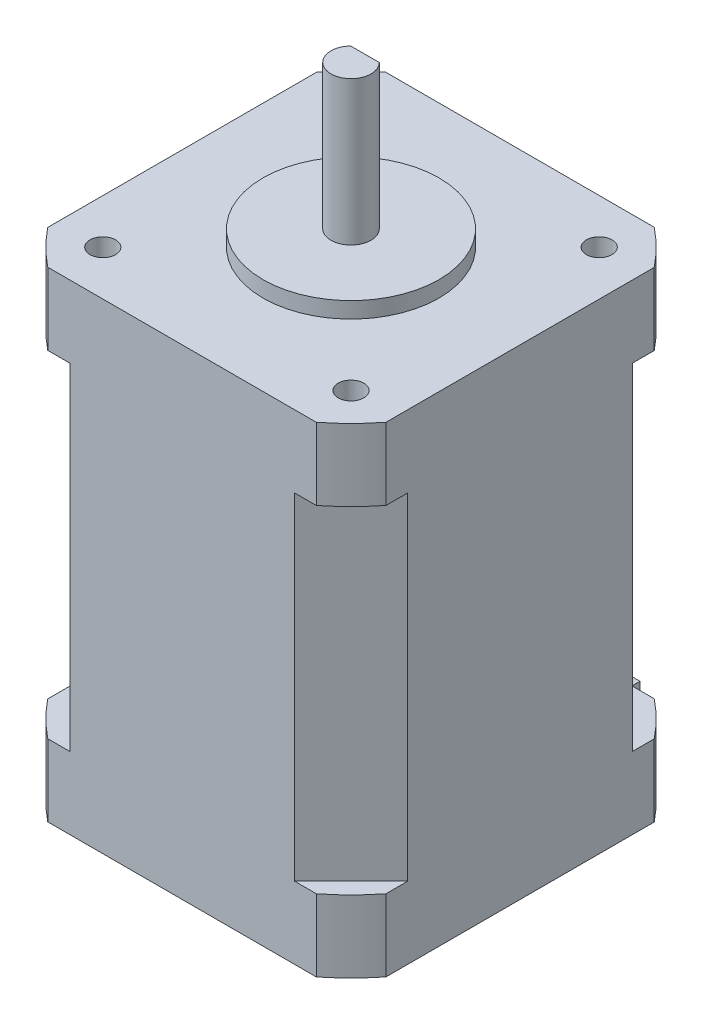
SolidWorks part; units mm, degrees
ref_plane "前视基准面" through (0, 0, 0) normal (0, 0, 1) x (1, 0, 0)
ref_plane "上视基准面" through (0, 0, 0) normal (0, 1, 0) x (1, 0, 0)
ref_plane "右视基准面" through (0, 0, 0) normal (1, 0, 0) x (0, 0, -1)
other "Configuration Table"
sketch "草图2" plane through (0, 0, 0) normal (0, 1, 0) x (1, 0, 0)
  line L0 (-14.0127, 22.4478) -> (-21.0838, 15.3767)
  line L1 (-14.0127, -19.7522) -> (14.0451, -19.7522)
  line L2 (-21.0838, -12.6812) -> (-21.0838, 15.3767)
  line L3 (-14.0127, 22.4478) -> (14.0451, 22.4478)
  line L4 (21.1162, -12.6812) -> (21.1162, 15.3767)
  line L5 (-18.4442, -15.3208) -> (19.9343, 16.5586) construction
  line L6 (-17.2245, 19.2359) -> (15.9664, -17.8309) construction
  line L7 (21.1162, 15.3767) -> (14.0451, 22.4478)
  line L8 (14.0451, -19.7522) -> (21.1162, -12.6812)
  line L9 (-21.0838, -12.6812) -> (-14.0127, -19.7522)
  point P0 (0, 0)
  point P17 (0.0162, 1.3478)
  dimension "D1" = 10
  dimension "D2" = 42.2
  dimension "D3" = 135
  dimension "D5" = 4
extrude "凸台-拉伸1" add sketch "草图2" along normal blind 60
sketch "草图5" plane through (0, 60, 0) normal (0, 1, 0) x (1, 0, 0)
  line L0 (21.1162, -12.6812) -> (21.1162, 15.3767) construction
  line L1 (-16.7762, 22.4478) -> (16.7762, 22.4478)
  line L2 (-21.0838, 18.1444) -> (-21.0838, -15.4488)
  line L3 (-16.7762, -19.7522) -> (16.7762, -19.7522)
  line L4 (21.1162, 18.1036) -> (21.1162, -15.4081)
  line L5 (14.0451, 22.4478) -> (-14.0127, 22.4478) construction
  line L6 (-21.0838, 15.3767) -> (-21.0838, -12.6812) construction
  line L7 (-14.0127, -19.7522) -> (14.0451, -19.7522) construction
  arc A0 (-16.7762, 22.4478) -> (-21.0838, 18.1444) centre (0, 1.3478) ccw
  arc A1 (-21.0838, -15.4488) -> (-16.7762, -19.7522) centre (0, 1.3478) ccw
  arc A2 (16.7762, -19.7522) -> (21.1162, -15.4081) centre (0, 1.3478) ccw
  arc A3 (21.1162, 18.1036) -> (16.7762, 22.4478) centre (0, 1.3478) ccw
  dimension "D1" = 21.1
extrude "凸台-拉伸2" add sketch "草图5" against normal blind 9 contours A3 L1 A0 L2 A1 L3 A2 L4
ref_plane "基准面1" through (0, 30, 0) normal (0, 1, 0) x (1, 0, 0)
mirror "镜向1" about plane through (0, 30, 0) normal (0, 1, 0) of "凸台-拉伸2"
sketch "草图7" plane through (0, 60, 0) normal (0, 1, 0) x (1, 0, 0)
  line L0 (16.7762, 22.4478) -> (-16.7762, 22.4478) construction
  circle A0 centre (0, 1.3478) radius 11
  dimension "D1" = 22
  dimension "D2" = 21.1
extrude "凸台-拉伸3" add sketch "草图7" along normal blind 2
sketch "草图8" plane through (0, 62, 0) normal (0, 1, 0) x (1, 0, 0)
  line L0 (16.7762, 22.4478) -> (-16.7762, 22.4478) construction
  circle A0 centre (0, 1.3478) radius 2.5
  dimension "D1" = 5
  dimension "D2" = 21.1
extrude "凸台-拉伸4" add sketch "草图8" along normal blind 18
sketch "草图9" plane through (0, 80, 0) normal (0, 1, 0) x (1, 0, 0)
  line L0 (-1.7854, 3.0978) -> (1.7854, 3.0978)
  arc A0 (1.7854, 3.0978) -> (-1.7854, 3.0978) centre (0, 1.3478) ccw
  dimension "D1" = 1.75
extrude "切除-拉伸1" cut sketch "草图9" against normal blind 15
sketch "草图10" plane through (0, 60, 0) normal (0, 1, 0) x (1, 0, 0)
  circle A0 centre (-15.5, 16.8478) radius 1.6
  circle A2 centre (15.5, 16.8478) radius 1.6
  circle A3 centre (15.5, -14.1522) radius 1.6
  circle A4 centre (-15.5, -14.1522) radius 1.6
  point P2 (0, 1.3478)
  point P13 (0, 1.3478)
  dimension "D1" = 3.2
  dimension "D2" = 15.5
  dimension "D3" = 15.5
  dimension "D4" = 4
extrude "切除-拉伸2" cut sketch "草图10" against normal blind 4.5
sketch "草图11" plane through (0, 0, -22.4478) normal (0, 0, -1) x (-1, 0, 0)
  line L0 (10, 0) -> (-10, 0)
  line L1 (-16.7762, 0) -> (16.7762, 0) construction
  line L2 (-10, 0) -> (-10, 5)
  line L3 (-10, 5) -> (-9, 5)
  line L4 (-9, 5) -> (-9, 1)
  line L5 (-9, 1) -> (9, 1)
  line L6 (0, 0) -> (0, 4.3168) construction
  line L7 (9, 5) -> (9, 1)
  line L8 (10, 5) -> (9, 5)
  line L9 (10, 0) -> (10, 5)
  point P11 (0, 1)
  dimension "D1" = 1
  dimension "D2" = 20
  dimension "D3" = 5
  dimension "D4" = 1
extrude "凸台-拉伸5" add sketch "草图11" along normal blind 5
sketch "草图12" plane through (0, 0, 0) normal (0, -1, 0) x (1, 0, 0)
  line L0 (-7.1447, -27.4478) -> (-7.1447, -24.4478)
  line L1 (10, -27.4478) -> (-10, -27.4478) construction
  line L2 (-7.1447, -24.4478) -> (-7.6447, -24.4478)
  line L3 (-7.6447, -24.4478) -> (-7.6447, -26.4478)
  line L4 (-7.6447, -26.4478) -> (-8.1447, -26.4478)
  line L5 (-8.1447, -26.4478) -> (-7.6447, -27.4478)
  line L6 (-7.6447, -27.4478) -> (-7.1447, -27.4478)
  line L7 (0, -27.6121) -> (0, -20.757) construction
  line L8 (7.6447, -27.4478) -> (7.1447, -27.4478)
  line L9 (8.1447, -26.4478) -> (7.6447, -27.4478)
  line L10 (7.6447, -26.4478) -> (8.1447, -26.4478)
  line L11 (7.6447, -24.4478) -> (7.6447, -26.4478)
  line L12 (7.1447, -24.4478) -> (7.6447, -24.4478)
  line L13 (7.1447, -27.4478) -> (7.1447, -24.4478)
  dimension "D1" = 0.5
  dimension "D2" = 0.5
  dimension "D3" = 0.5
  dimension "D4" = 1
  dimension "D5" = 3
extrude "切除-拉伸3" cut sketch "草图12" against normal blind 5
sketch "草图13" plane through (0, 0, -22.4478) normal (0, 0, -1) x (-1, 0, 0)
  line L0 (0, 0) -> (0, 8.1139) construction
  line L1 (9, 1) -> (-9, 1) construction
  circle A0 centre (-1.27, 3.54) radius 0.5623
  circle A1 centre (-3.81, 3.54) radius 0.5623
  circle A2 centre (-6.35, 3.54) radius 0.5623
  circle A3 centre (6.35, 3.54) radius 0.5623
  circle A4 centre (3.81, 3.54) radius 0.5623
  circle A5 centre (1.27, 3.54) radius 0.5623
  dimension "D1" = 2.54
  dimension "D3" = 2.54
  dimension "D2" = 3
extrude "凸台-拉伸6" add sketch "草图13" along normal blind 5
sketch "草图14" plane through (0, 0, 0) normal (0, -1, 0) x (1, 0, 0)
  line L0 (21.1162, 15.4081) -> (21.1162, -18.1036) construction
  circle A0 centre (14.1162, 12.7522) radius 2
  circle A1 centre (12.7522, -14.1162) radius 2
  circle A2 centre (-14.1162, -12.7522) radius 2
  circle A3 centre (-12.7522, 14.1162) radius 2
  circle A4 centre (14.1162, 12.7522) radius 1.75
  circle A5 centre (12.7522, -14.1162) radius 1.75
  circle A6 centre (-14.1162, -12.7522) radius 1.75
  circle A7 centre (-12.7522, 14.1162) radius 1.75
  point P14 (0, 0)
  point P22 (0, 0)
  dimension "D4" = 4
  dimension "D5" = 3.5
  dimension "D1" = 7
  dimension "D2" = 7
  dimension "D3" = 4
  dimension "D6" = 4
extrude "切除-拉伸4" cut sketch "草图14" against normal blind 1
